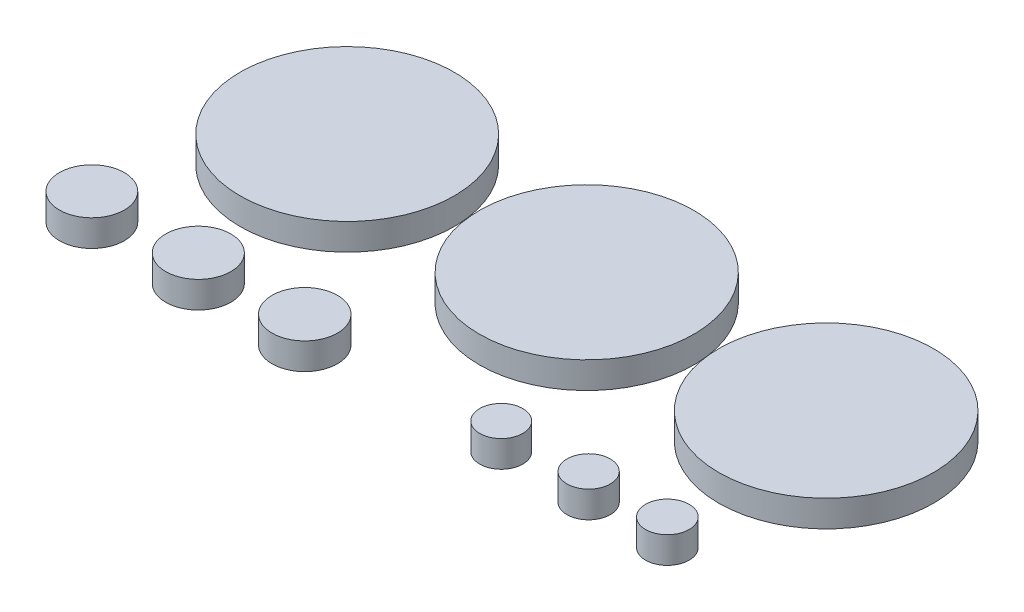
SolidWorks part; units mm, degrees
ref_plane "Front Plane" through (0, 0, 0) normal (0, 0, 1) x (1, 0, 0)
ref_plane "Top Plane" through (0, 0, 0) normal (0, 1, 0) x (1, 0, 0)
ref_plane "Right Plane" through (0, 0, 0) normal (1, 0, 0) x (0, 0, -1)
sketch "Sketch1" plane through (0, 0, 0) normal (0, 1, 0) x (1, 0, 0)
  circle A0 centre (-39.1807, 31.1665) radius 20.125
  circle A1 centre (5.8193, 31.1665) radius 20.15
  circle A2 centre (50.8193, 31.1665) radius 20.175
  circle A3 centre (-53.8472, -2.1407) radius 6.1
  circle A4 centre (-33.8472, -2.1407) radius 6.125
  circle A5 centre (-13.8472, -2.1407) radius 6.15
  circle A6 centre (21.9853, -1.0549) radius 4.05
  circle A7 centre (38.4086, -1.0549) radius 4.075
  circle A8 centre (53.2031, -1.0549) radius 4.1
  dimension "D1" = 40.25
  dimension "D2" = 40.3
  dimension "D3" = 40.35
  dimension "D6" = 12.2
  dimension "D7" = 12.25
  dimension "D8" = 12.3
  dimension "D11" = 8.1
  dimension "D12" = 8.15
  dimension "D13" = 8.2
  dimension "D4" = 45
  dimension "D5" = 45
  dimension "D9" = 20
  dimension "D10" = 20
extrude "Boss-Extrude1" add sketch "Sketch1" along normal blind 5
